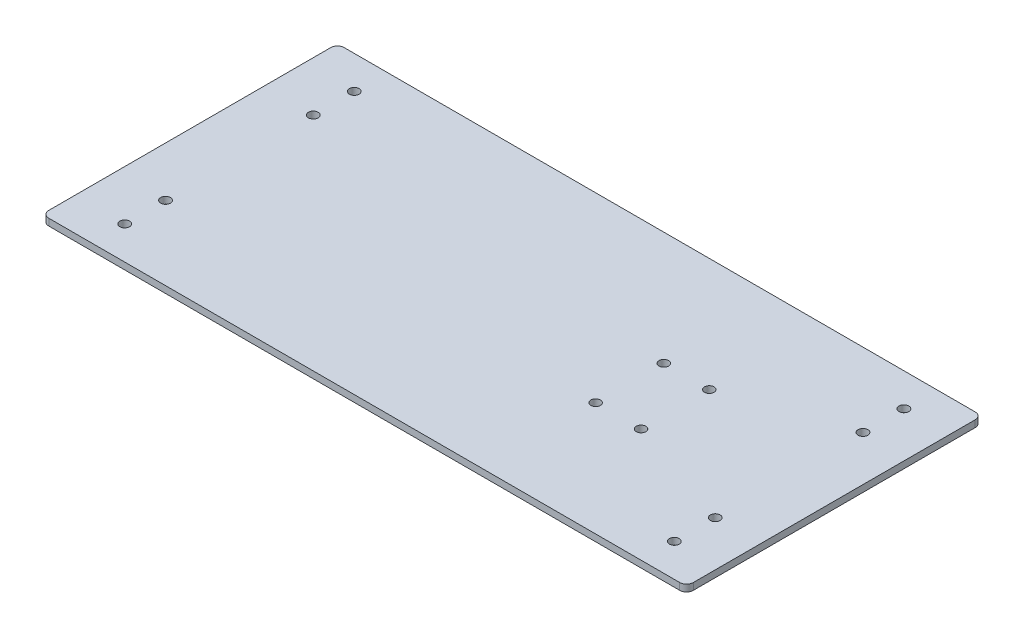
SolidWorks part; units mm, degrees
ref_plane "前视基准面" through (0, 0, 0) normal (0, 0, 1) x (1, 0, 0)
ref_plane "上视基准面" through (0, 0, 0) normal (0, 1, 0) x (1, 0, 0)
ref_plane "右视基准面" through (0, 0, 0) normal (1, 0, 0) x (0, 0, -1)
other "Configuration Table"
sketch "草图1" plane through (0, 0, 0) normal (0, 1, 0) x (1, 0, 0)
  line L0 (-119.925, 115.8547) -> (-119.925, -126.0855) construction
  line L1 (-141.79, -55.5) -> (141.79, -55.5)
  line L2 (-141.79, -55.5) -> (-141.79, 55.5)
  line L3 (-141.79, 55.5) -> (141.79, 55.5)
  line L4 (141.79, -55.5) -> (141.79, 55.5)
  line L5 (-141.79, -55.5) -> (141.79, 55.5) construction
  line L6 (-141.79, 55.5) -> (141.79, -55.5) construction
  line L7 (121.925, 112.9807) -> (121.925, -133.4012) construction
  line L8 (-187.7195, 0) -> (262.1572, 0) construction
  line L9 (0, 177.9163) -> (0, -142.7804) construction
  circle A0 centre (121.925, 50.5) radius 2.15
  circle A1 centre (121.925, 32.5) radius 2.15
  circle A2 centre (121.925, -32.5) radius 2.15
  circle A3 centre (121.925, -50.5) radius 2.15
  circle A4 centre (-119.925, 50.52) radius 2.15
  circle A5 centre (-119.925, 32.5) radius 2.15
  circle A6 centre (-119.925, -32.5) radius 2.15
  circle A7 centre (-119.925, -50.48) radius 2.15
  point P0 (0, 0)
  dimension "D3" = 65
  dimension "D4" = 101
  dimension "D5" = 4.3
  dimension "D6" = 4.3
  dimension "D7" = 4.3
  dimension "D8" = 4.3
  dimension "D9" = 4.3
  dimension "D10" = 4.3
  dimension "D11" = 4.3
  dimension "D12" = 4.3
  dimension "D13" = 65
  dimension "D14" = 101
  dimension "D18" = 50.52
  dimension "D19" = 32.5
  dimension "D1" = 241.85
  dimension "D2" = 283.58
  dimension "D15" = 111
  dimension "D16" = 32.5
  dimension "D17" = 50.5
  dimension "D20" = 119.925
extrude "凸台-拉伸1" add sketch "草图1" along normal blind 3
sketch "草图2" plane through (0, 0, 0) normal (0, -1, 0) x (-1, 0, 0)
  line L0 (-141.79, -55.5) -> (-141.79, 55.5) construction
  line L1 (141.79, -55.5) -> (-141.79, -55.5)
  line L2 (141.79, -55.5) -> (141.79, -65)
  line L3 (141.79, -65) -> (-141.79, -65)
  line L4 (-141.79, -55.5) -> (-141.79, -65)
  line L5 (141.79, 55.5) -> (-141.79, 55.5)
  line L6 (141.79, 55.5) -> (141.79, 65)
  line L7 (141.79, 65) -> (-141.79, 65)
  line L8 (-141.79, 55.5) -> (-141.79, 65)
  dimension "D1" = 130
extrude "凸台-拉伸2" add sketch "草图2" against normal blind 3
fillet "圆角1" radius 3 4 edges at (141.79, 1.5, 65) (-141.79, 1.5, 65) (-141.79, 1.5, -65) (141.79, 1.5, -65)
sketch "草图3" plane through (0, 0, 0) normal (0, -1, 0) x (-1, 0, 0)
  line L0 (-141.79, 0) -> (141.79, 0) construction
  line L1 (-138.79, -65) -> (138.79, -65) construction
  line L2 (138.79, 65) -> (-138.79, 65) construction
  line L3 (-61.79, -65) -> (-61.79, 65) construction
  line L4 (-141.79, -62) -> (-141.79, 62) construction
  line L5 (141.79, 62) -> (141.79, -62) construction
  circle A0 centre (-71.79, -15) radius 2.1
  circle A1 centre (-51.79, -15) radius 2.1
  circle A2 centre (-51.79, 15) radius 2.1
  circle A3 centre (-71.79, 15) radius 2.1
  dimension "D2" = 4.2
  dimension "D1" = 80
  dimension "D3" = 30
  dimension "D4" = 20
extrude "切除-拉伸1" cut sketch "草图3" against normal blind 10
